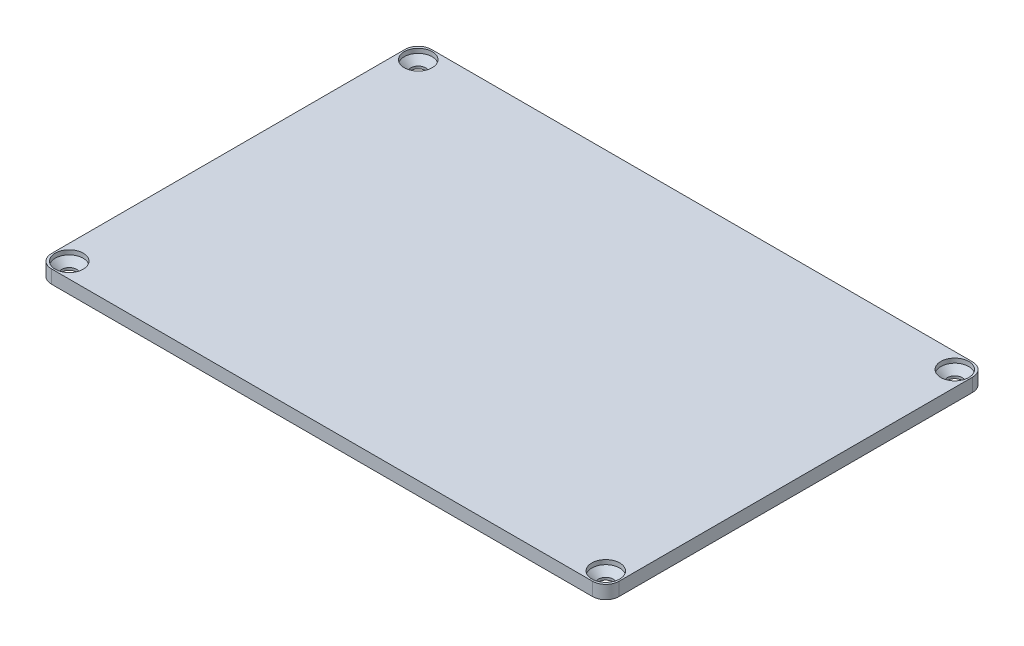
SolidWorks part; units mm, degrees
ref_plane "Front Plane" through (0, 0, 0) normal (0, 0, 1) x (1, 0, 0)
ref_plane "Top Plane" through (0, 0, 0) normal (0, 1, 0) x (1, 0, 0)
ref_plane "Right Plane" through (0, 0, 0) normal (1, 0, 0) x (0, 0, -1)
sketch "Sketch1" plane through (0, 0, 0) normal (0, 1, 0) x (1, 0, 0)
  line L1 (-64, -42.85) -> (64, -42.85)
  line L2 (-64, -42.85) -> (-64, 42.85)
  line L3 (-64, 42.85) -> (64, 42.85)
  line L4 (64, -42.85) -> (64, 42.85)
  line L5 (-64, -42.85) -> (64, 42.85) construction
  line L6 (-64, 42.85) -> (64, -42.85) construction
  point P0 (0, 0)
  dimension "D1" = 85.7
  dimension "D2" = 128
extrude "Boss-Extrude1" add sketch "Sketch1" along normal blind 3
hole_wizard "CSK for M3 Flat Head Machine Screw1" positions "Sketch2" profile "Sketch3" countersink size "M3" standard "ANSI Metric"
sketch "Sketch2" plane through (0, 3, 0) normal (0, 1, 0) x (1, 0, 0)
  line L2 (64, 42.85) -> (-64, 42.85) construction
  line L3 (-64, 42.85) -> (-64, -42.85) construction
  line L4 (64, -42.85) -> (64, 42.85) construction
  line L5 (-64, -42.85) -> (64, -42.85) construction
  point P0 (-60.5, 39.35)
  point P6 (60.5, 39.35)
  point P12 (60.5, -39.35)
  point P16 (-60.5, -39.35)
  dimension "D1" = 3.5
  dimension "D2" = 3.5
  dimension "D3" = 3.5
  dimension "D4" = 3.5
sketch "Sketch3" plane through (-60.5, 3, -39.35) normal (1, 0, 0) x (0, 0, 1)
  line L0 (0, 0) -> (0, 4.0215)
  line L1 (0, 4.0215) -> (1.7, 3)
  line L2 (1.7, 3) -> (1.7, 2.45)
  line L3 (1.7, 2.45) -> (3.15, 1)
  line L4 (3.15, 1) -> (3.15, 0)
  line L6 (3.15, 0) -> (0, 0)
  line L7 (-1.7, 2.45) -> (-3.15, 1) construction
  line L10 (0, 4.0215) -> (-1.7, 3) construction
  line L11 (0, -6.35) -> (0, 107.95) construction
  dimension "Hole Dia." = 3.4
  dimension "Hole Depth" = 3
  dimension "C'Sink Dia." = 6.3
  dimension "C'Sink Angle" = 90
  dimension "Drill Angle" = 118
  dimension "Head Clearance" = 1
fillet "Fillet1" radius 3 4 edges at (64, 1.5, -42.85) (64, 1.5, 42.85) (-64, 1.5, -42.85) (-64, 1.5, 42.85)
equation "\"D2@Sketch2\"=\"D1@Sketch2\""
equation "\"D3@Sketch2\"=\"D1@Sketch2\""
equation "\"D4@Sketch2\"=\"D1@Sketch2\""
